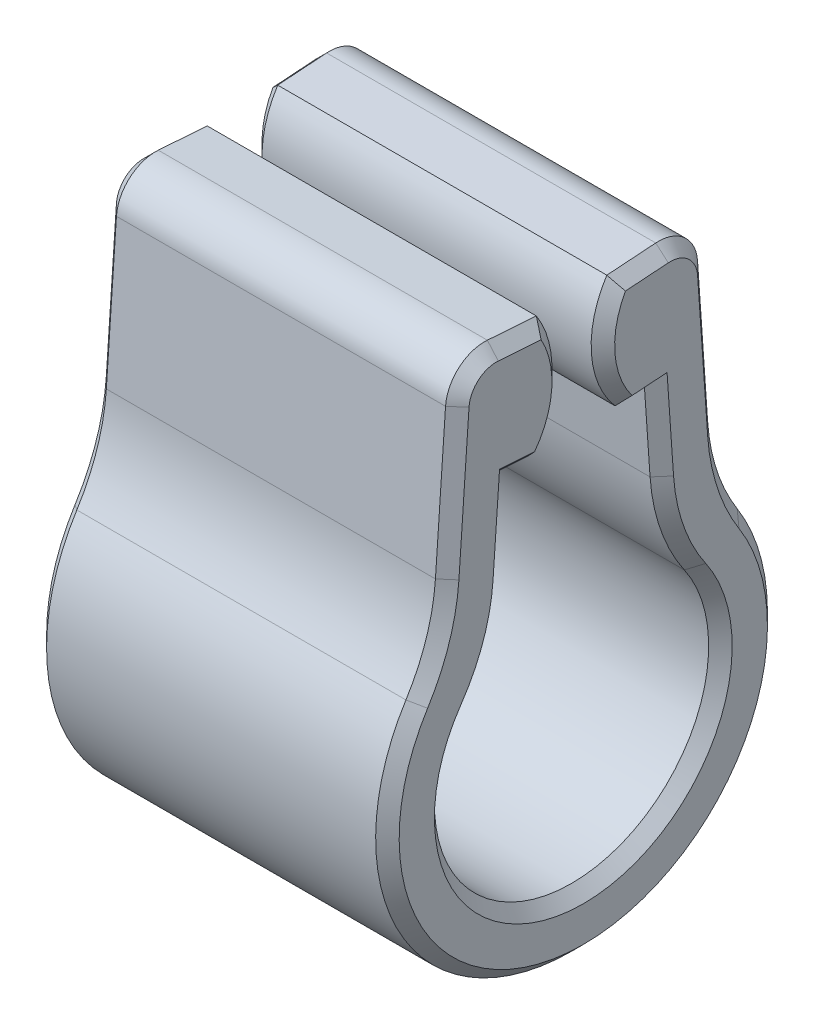
SolidWorks part; units mm, degrees
ref_plane "Front Plane" through (0, 0, 0) normal (0, 0, 1) x (1, 0, 0)
ref_plane "Top Plane" through (0, 0, 0) normal (0, 1, 0) x (1, 0, 0)
ref_plane "Right Plane" through (0, 0, 0) normal (1, 0, 0) x (0, 0, -1)
sketch "Sketch2" plane through (-5, 5, -3) normal (-1, 0, 0) x (0, 1, 0)
  line L15 (22.0983, 0) -> (-2.6189, 0) construction
  line L18 (19.4908, 1) -> (6.5092, 1) construction
  line L20 (13.3811, -2.0097) -> (13.6952, -6.5024) construction
  line L22 (19.4908, -1) -> (6.5092, -1) construction
  line L25 (16.3738, 1.8005) -> (16.6879, 6.2932)
  line L26 (16.6879, 6.2932) -> (7.319, 6.9483)
  line L27 (10.3884, 2.219) -> (10.4933, 3.719)
  line L28 (10.4933, 3.719) -> (6.3498, 4.0088)
  line L29 (10.3884, 2.219) -> (16.3738, 1.8005) construction
  line L41 (16.6879, 6.2932) -> (23.4389, 6.2932) construction
  line L42 (13.3811, 2.0097) -> (13.6952, 6.5024) construction
  line L43 (10.3884, -2.219) -> (16.3738, -1.8005) construction
  line L45 (10.4933, -3.719) -> (6.3498, -4.0088)
  line L46 (10.3884, -2.219) -> (10.4933, -3.719)
  line L47 (16.6879, -6.2932) -> (7.319, -6.9483)
  line L48 (16.3738, -1.8005) -> (16.6879, -6.2932)
  arc A1 (2.7216, -8.4545) -> (2.7216, 8.4545) centre (-2.6189, 0) cw
  arc A4 (1.3613, -5.7583) -> (1.3613, 5.7583) centre (-2.6189, 0) cw
  arc A5 (1.3613, 5.7583) -> (6.3498, 4.0088) centre (7.0473, 13.9844) ccw
  arc A6 (2.7216, 8.4545) -> (7.319, 6.9483) centre (8.0097, 16.8259) ccw
  arc A10 (16.3738, 1.8005) -> (10.3884, 2.219) centre (13.6601, 6) cw
  arc A11 (16.3738, -1.8005) -> (10.3884, -2.219) centre (13.6601, -6) ccw
  arc A12 (2.7216, -8.4545) -> (7.319, -6.9483) centre (8.0097, -16.8259) cw
  arc A13 (1.3613, -5.7583) -> (6.3498, -4.0088) centre (7.0473, -13.9844) cw
  point P0 (0, 0)
  point P6 (0, 0)
  dimension "D1" = 3
  dimension "D6" = 2
  dimension "D4" = 5
  dimension "D10" = 10
  dimension "D14" = 10
  dimension "D2" = 1.5
  dimension "D3" = 3
  dimension "D5" = 16
  dimension "D7" = 3
  dimension "D13" = 6
  dimension "D15" = 94
extrude "Boss-Extrude1" add sketch "Sketch2" along normal blind 18
fillet "Fillet1" radius 2 2 edges at (-14, 21.6879, -9.2932) (-14, 21.6879, 3.2932)
chamfer "Chamfer1" distance 0.6 angle 45 36 edges at (-5, 18.3113, -4.0122) (-5, 15.4408, -5.969) (-5, 13.4215, -6.8639) (-5, 8.7378, -7.5479) (-5, -4.6189, -3) (-23, -7.6189, -3) (-23, 9.9269, -10.4163) (-23, 16.0059, -9.6905) (-23, 21.0627, -8.7497) (-23, 21.4611, -6.0493) (-23, 18.3113, -4.0122) (-23, 15.4408, -5.969) (-23, 13.4215, -6.8639) (-23, 8.7378, -7.5479) (-23, -4.6189, -3) (-5, 21.4611, -6.0493) (-5, 21.0627, -8.7497) (-5, 16.0059, -9.6905) (-5, 9.9269, -10.4163) (-5, -7.6189, -3) (-23, 8.7378, 1.5479) (-23, 13.4215, 0.8639) (-23, 15.4408, -0.031) (-23, 18.3113, -1.9878) (-23, 21.4611, 0.0493) (-23, 16.0059, 3.6905) (-23, 9.9269, 4.4163) (-5, 9.9269, 4.4163) (-5, 16.0059, 3.6905) (-5, 21.4611, 0.0493) (-5, 18.3113, -1.9878) (-5, 15.4408, -0.031) (-5, 13.4215, 0.8639) (-5, 8.7378, 1.5479) (-23, 21.0627, 2.7497) (-5, 21.0627, 2.7497)
